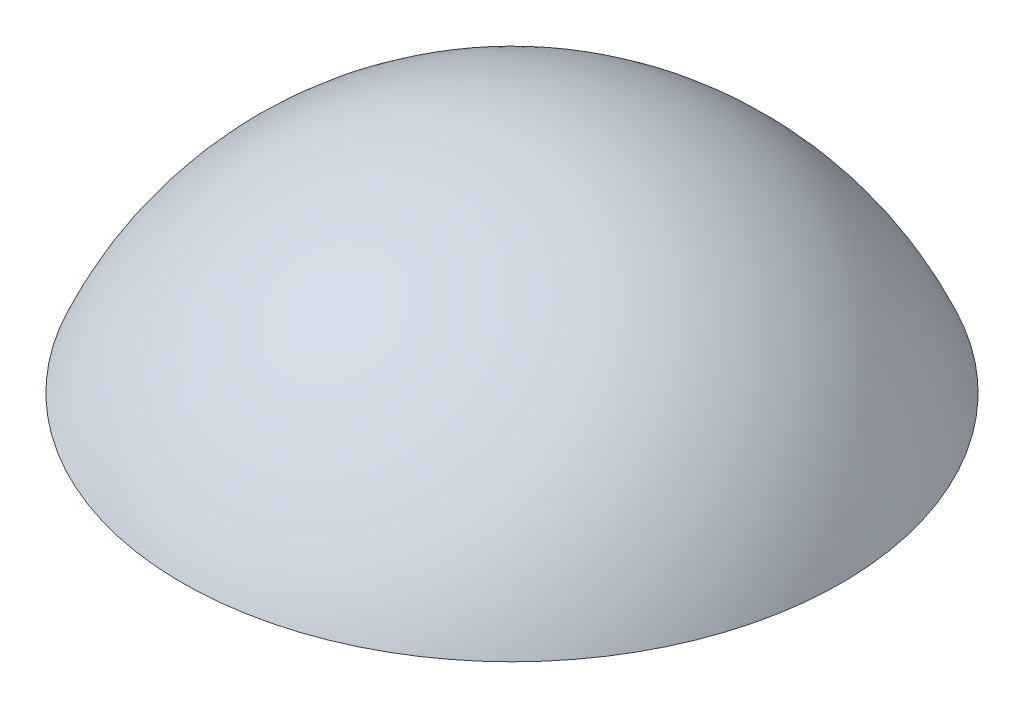
SolidWorks part; units mm, degrees
ref_plane "Front Plane" through (0, 0, 0) normal (0, 0, 1) x (1, 0, 0)
ref_plane "Top Plane" through (0, 0, 0) normal (0, 1, 0) x (1, 0, 0)
ref_plane "Right Plane" through (0, 0, 0) normal (1, 0, 0) x (0, 0, -1)
sketch "Sketch1" plane through (0, 0, 0) normal (0, 0, 1) x (1, 0, 0)
  line L0 (0, -20.0987) -> (0, 174.3701) construction
  line L1 (0, 0) -> (-352.5428, 0) construction
  line L2 (-3, 1.2475) -> (79.129, 143.4991) construction
  line L3 (-3, 1.2475) -> (0, 1.2475)
  line L4 (0, 1.2475) -> (0, 3.249)
  arc A0 (-3, 1.2475) -> (0, 3.249) centre (0, 0) cw
  dimension "D2" = 3
  dimension "D1" = 60
revolve "Revolve1" add sketch "Sketch1" angle 360 about L4
